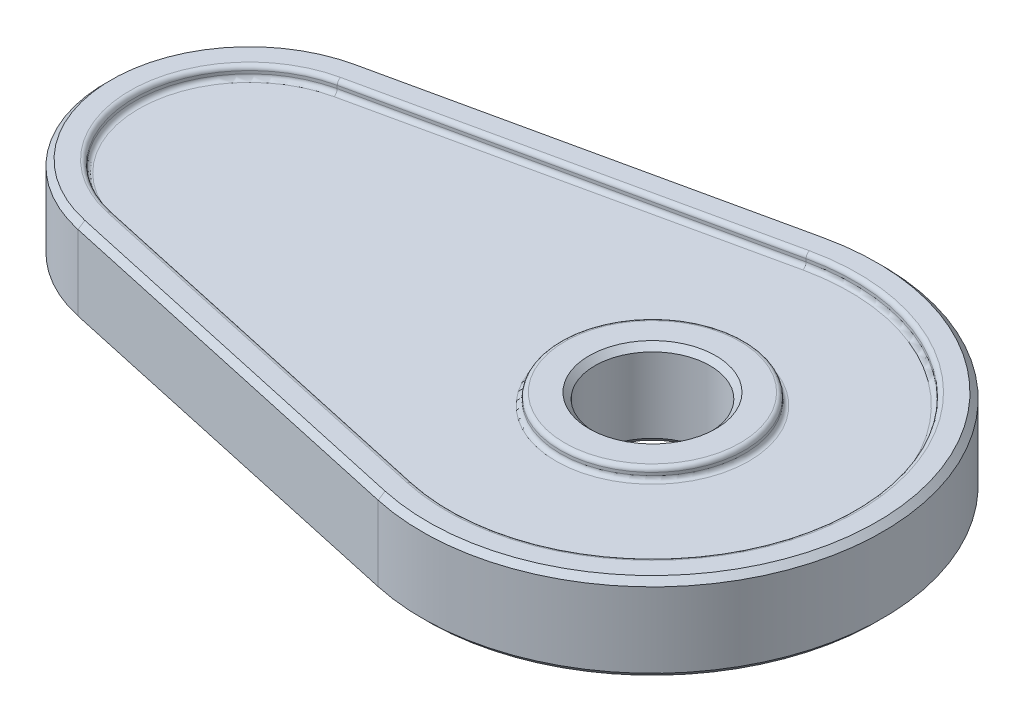
SolidWorks part; units mm, degrees
ref_plane "Front Plane" through (0, 0, 0) normal (0, 0, 1) x (1, 0, 0)
ref_plane "Top Plane" through (0, 0, 0) normal (0, 1, 0) x (1, 0, 0)
ref_plane "Right Plane" through (0, 0, 0) normal (1, 0, 0) x (0, 0, -1)
sketch "Sketch1" plane through (0, 0, 0) normal (0, 1, 0) x (1, 0, 0)
  line L0 (-75.3571, 24.4193) -> (-8.5714, 39.0708)
  line L1 (-75.3571, -24.4193) -> (-8.5714, -39.0708)
  arc A0 (-8.5714, -39.0708) -> (-8.5714, 39.0708) centre (0, 0) ccw
  circle A1 centre (0, 0) radius 10
  arc A2 (-75.3571, 24.4193) -> (-75.3571, -24.4193) centre (-70, 0) ccw
  dimension "D1" = 80
  dimension "D2" = 20
  dimension "D3" = 50
  dimension "D4" = 70
extrude "Boss-Extrude1" add sketch "Sketch1" along normal mid plane 15
chamfer "Chamfer1" distance 1 angle 45 8 edges at (-95, -7.5, 0) (-41.9643, -7.5, 31.7451) (-41.9643, -7.5, -31.7451) (40, -7.5, 0) (-95, 7.5, 0) (-41.9643, 7.5, 31.7451) (-41.9643, 7.5, -31.7451) (40, 7.5, 0)
chamfer "Chamfer2" distance 1 angle 45 2 edges at (0, -7.5, 10) (0, 7.5, 10)
sketch "Sketch2" plane through (0, 7.5, 0) normal (0, 1, 0) x (1, 0, 0)
  line L0 (-8.5714, -39.0708) -> (-75.3571, -24.4193) construction
  line L1 (-75.3571, 24.4193) -> (-8.5714, 39.0708) construction
  line L2 (-8.5714, -39.0708) -> (-75.3571, -24.4193)
  line L3 (-75.3571, 24.4193) -> (-8.5714, 39.0708)
  line L4 (-74.2857, 19.5354) -> (-7.5, 34.187)
  line L5 (-7.5, -34.187) -> (-74.2857, -19.5354)
  arc A0 (-8.5714, -39.0708) -> (-8.5714, 39.0708) centre (0, 0) ccw construction
  arc A1 (-75.3571, 24.4193) -> (-75.3571, -24.4193) centre (-70, 0) ccw construction
  arc A2 (-8.5714, -39.0708) -> (-8.5714, 39.0708) centre (0, 0) ccw
  arc A3 (-75.3571, 24.4193) -> (-75.3571, -24.4193) centre (-70, 0) ccw
  circle A4 centre (0, 0) radius 11 construction
  circle A5 centre (0, 0) radius 11
  arc A6 (-7.5, -34.187) -> (-7.5, 34.187) centre (0, 0) ccw
  arc A7 (-74.2857, 19.5354) -> (-74.2857, -19.5354) centre (-70, 0) ccw
  circle A8 centre (0, 0) radius 16
  dimension "D1" = 5
  dimension "D2" = 5
extrude "Cut-Extrude1" cut sketch "Sketch2" against normal blind 2 contours L4 A7 L5 A6 A8
mirror "Mirror2" about plane through (0, 0, 0) normal (0, 1, 0) of "Cut-Extrude1"
fillet "Fillet1" radius 0.75 20 edges at (-40.8929, -5.5, -26.8612) (35, -5.5, 0) (-40.8929, -5.5, 26.8612) (-40.8929, -7.5, -26.8612) (35, -7.5, 0) (-40.8929, -7.5, 26.8612) (-40.8929, 5.5, -26.8612) (35, 5.5, 0) (-40.8929, 5.5, 26.8612) (-40.8929, 7.5, -26.8612) (35, 7.5, 0) (-40.8929, 7.5, 26.8612) (-90, -5.5, 0) (-90, -7.5, 0) (-90, 5.5, 0) (-90, 7.5, 0) (0, -7.5, 16) (0, -5.5, 16) (0, 7.5, 16) (0, 5.5, 16)
